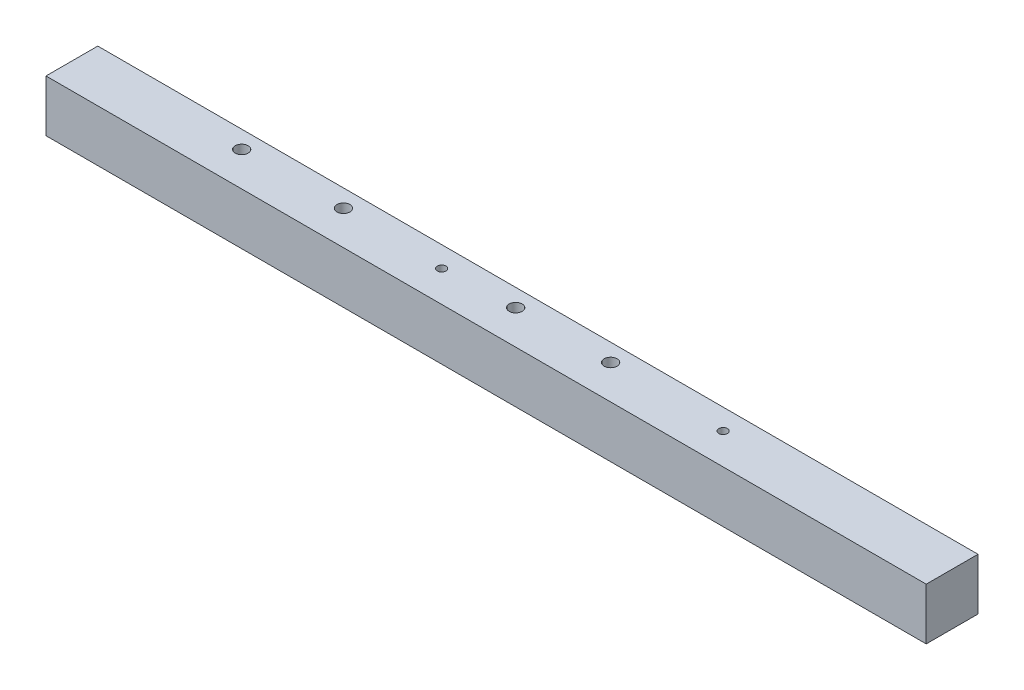
SolidWorks part; units mm, degrees
ref_plane "Front Plane" through (0, 0, 0) normal (0, 0, 1) x (1, 0, 0)
ref_plane "Top Plane" through (0, 0, 0) normal (0, 1, 0) x (1, 0, 0)
ref_plane "Right Plane" through (0, 0, 0) normal (1, 0, 0) x (0, 0, -1)
sketch "Sketch1" plane through (0, 0, 0) normal (0, 1, 0) x (1, 0, 0)
  line L1 (0, 0) -> (647.7, 0)
  line L2 (0, 0) -> (0, 38.1)
  line L3 (0, 38.1) -> (647.7, 38.1)
  line L4 (647.7, 0) -> (647.7, 38.1)
  circle A0 centre (118.8022, 25.146) radius 4.7625
  circle A1 centre (193.7322, 25.146) radius 4.7625
  circle A2 centre (320.4706, 25.146) radius 4.7625
  circle A3 centre (390.3206, 25.146) radius 4.7625
  circle A4 centre (268.2541, 22.8376) radius 3.175
  circle A5 centre (475.3911, 22.8376) radius 3.175
  dimension "D3" = 9.525
  dimension "D5" = 9.525
  dimension "D6" = 126.7384
  dimension "D7" = 69.85
  dimension "D8" = 9.525
  dimension "D9" = 9.525
  dimension "D11" = 6.35
  dimension "D12" = 6.35
  dimension "D1" = 38.1
  dimension "D2" = 647.7
  dimension "D4" = 74.93
  dimension "D10" = 207.137
  dimension "D13" = 15.2624
  dimension "D14" = 12.954
  dimension "D15" = 268.2541
extrude "Boss-Extrude1" add sketch "Sketch1" along normal blind 38.1
sketch "Sketch2" plane through (0, 38.1, 0) normal (0, 1, 0) x (1, 0, 0)
  line L0 (231.7774, 29.7419) -> (231.7774, 12.5045)
  line L1 (438.9144, 28.4445) -> (438.9144, 12.5045)
  dimension "D1" = 207.137
